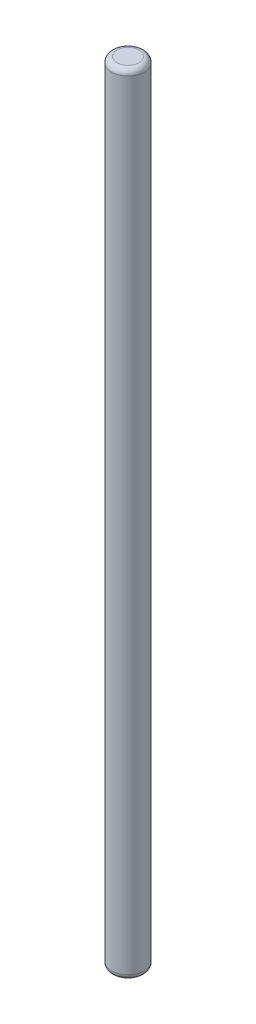
SolidWorks part; units mm, degrees
material "Stainless Steel (ferritic)"
ref_plane "Ön Düzlem" through (0, 0, 0) normal (0, 0, 1) x (1, 0, 0)
ref_plane "Üst Düzlem" through (0, 0, 0) normal (0, 1, 0) x (1, 0, 0)
ref_plane "Sağ Düzlem" through (0, 0, 0) normal (1, 0, 0) x (0, 0, -1)
sketch "Çizim1" plane through (0, 0, 0) normal (0, 1, 0) x (1, 0, 0)
  circle A0 centre (0, 0) radius 1.5
  dimension "D1" = 3
extrude "Yükseklik-Ekstrüzyon1" add sketch "Çizim1" along normal blind 72
fillet "Radyus1" radius 0.5 1 edges at (0, 72, 1.5)
fillet "Radyus2" radius 0.5 1 edges at (0, 0, 1.5)
